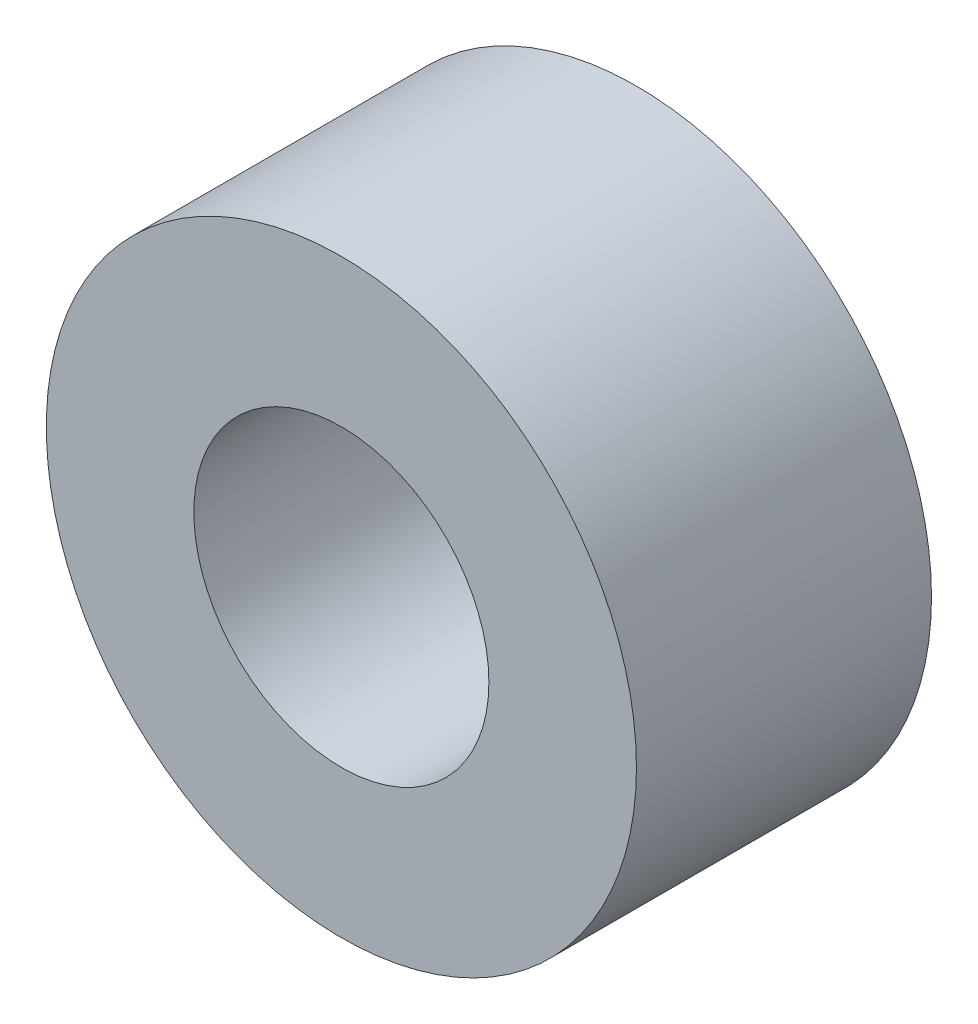
SolidWorks part; units mm, degrees
material "AISI 304"
ref_plane "前视基准面" through (0, 0, 0) normal (0, 0, 1) x (1, 0, 0)
ref_plane "上视基准面" through (0, 0, 0) normal (0, 1, 0) x (1, 0, 0)
ref_plane "右视基准面" through (0, 0, 0) normal (1, 0, 0) x (0, 0, -1)
other "Configuration Table"
sketch "草图1" plane through (0, 0, 0) normal (0, 0, 1) x (1, 0, 0)
  circle A0 centre (-5.059, 32.4814) radius 2
  circle A1 centre (-5.059, 32.4814) radius 1
  dimension "D1" = 4
  dimension "D2" = 2
extrude "凸台-拉伸1" add sketch "草图1" along normal blind 2
